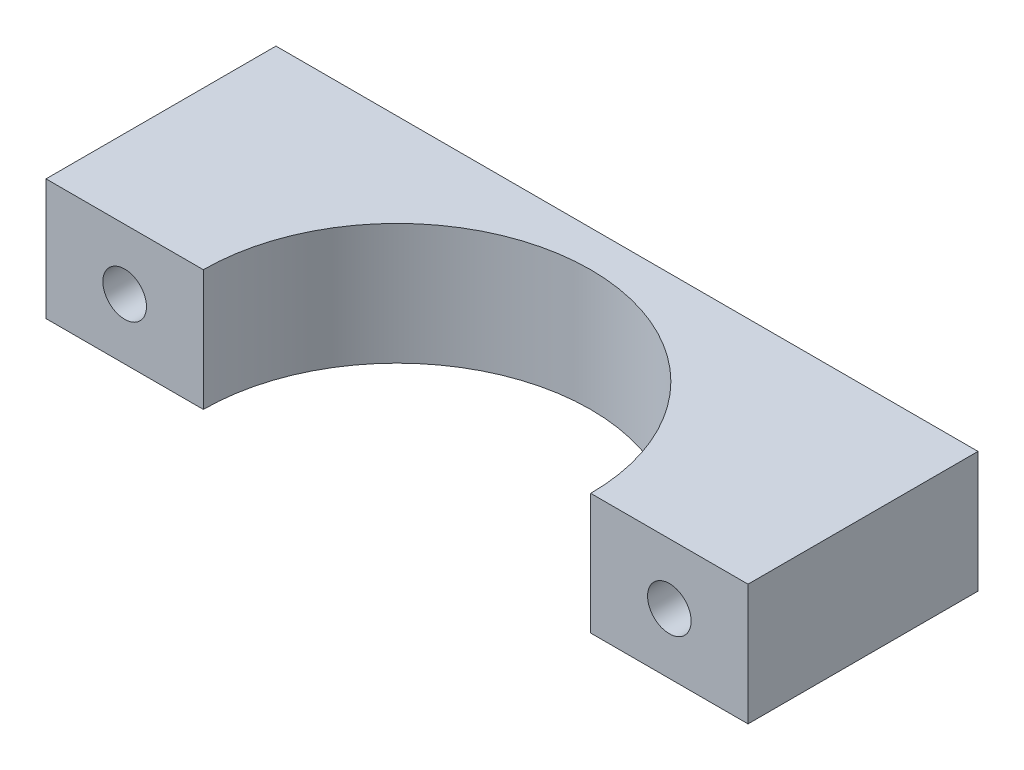
SolidWorks part; units mm, degrees
ref_plane "前视基准面" through (0, 0, 0) normal (0, 0, 1) x (1, 0, 0)
ref_plane "上视基准面" through (0, 0, 0) normal (0, 1, 0) x (1, 0, 0)
ref_plane "右视基准面" through (0, 0, 0) normal (1, 0, 0) x (0, 0, -1)
sketch "草图1" plane through (0, 0, 0) normal (0, 1, 0) x (1, 0, 0)
  line L0 (-29.8076, -12.4255) -> (-3.8076, -12.4255) construction
  line L2 (-69.3343, 8.5745) -> (-11.3343, 8.5745) construction
  line L3 (-69.3343, 8.5745) -> (-69.3343, 4.5745) construction
  line L4 (-69.3343, 4.5745) -> (-11.3343, 4.5745) construction
  line L5 (-11.3343, 8.5745) -> (-11.3343, 4.5745) construction
  line L8 (-69.3343, 6.5745) -> (-56.3343, 6.5745)
  line L10 (-11.3343, 6.5745) -> (-24.3343, 6.5745)
  line L11 (-69.3343, 6.5745) -> (-69.3343, 25.5745)
  line L12 (-69.3343, 25.5745) -> (-11.3343, 25.5745)
  line L13 (-11.3343, 25.5745) -> (-11.3343, 6.5745)
  circle A0 centre (-40.3343, 6.5745) radius 16 construction
  circle A1 centre (-40.3343, 6.5745) radius 19 construction
  arc A3 (-56.3343, 6.5745) -> (-24.3343, 6.5745) centre (-40.3343, 6.5745) cw
  point P9 (-69.3343, 6.5745)
  point P11 (-40.3343, 8.5745)
  dimension "D1" = 4
  dimension "D2" = 29
  dimension "D3" = 19
extrude "凸台-拉伸2" add sketch "草图1" along normal blind 10
sketch "草图8" plane through (0, 0, -6.5745) normal (0, 0, 1) x (1, 0, 0)
  line L0 (-69.3343, 10) -> (-56.3343, 10) construction
  line L1 (-69.3343, 10) -> (-69.3343, 0) construction
  line L2 (-24.3343, 10) -> (-11.3343, 10) construction
  line L3 (-11.3343, 10) -> (-11.3343, 0) construction
  circle A0 centre (-62.8343, 5) radius 1.8
  circle A1 centre (-17.8343, 5) radius 1.8
  point P0 (-62.8343, 10)
  point P1 (-69.3343, 5)
  point P4 (-17.8343, 10)
  point P7 (-11.3343, 5)
  point P10 (-17.8343, 5)
  point P13 (-62.8343, 5)
extrude "切除-拉伸3" cut sketch "草图8" against normal blind 5
sketch "草图9" plane through (0, 0, -25.5745) normal (0, 0, -1) x (-1, 0, 0)
  line L0 (11.3343, 10) -> (11.3343, 0) construction
  line L1 (11.3343, 5) -> (69.3343, 5) construction
  line L2 (69.3343, 10) -> (69.3343, 0) construction
  line L5 (20.7343, 2.1) -> (14.9343, 2.1)
  line L6 (20.7343, 2.1) -> (20.7343, 7.9)
  line L7 (20.7343, 7.9) -> (14.9343, 7.9)
  line L8 (14.9343, 2.1) -> (14.9343, 7.9)
  line L9 (20.7343, 2.1) -> (14.9343, 7.9) construction
  line L10 (20.7343, 7.9) -> (14.9343, 2.1) construction
  line L12 (59.9343, 7.9) -> (65.7343, 7.9)
  line L13 (59.9343, 7.9) -> (59.9343, 2.1)
  line L14 (59.9343, 2.1) -> (65.7343, 2.1)
  line L15 (65.7343, 7.9) -> (65.7343, 2.1)
  line L16 (59.9343, 7.9) -> (65.7343, 2.1) construction
  line L17 (59.9343, 2.1) -> (65.7343, 7.9) construction
  point P0 (11.3343, 5)
  point P7 (62.8343, 5)
  point P9 (17.8343, 5)
  dimension "D1" = 6.5
  dimension "D2" = 5.8
  dimension "D3" = 5.8
  dimension "D4" = 6.5
  dimension "D5" = 5.8
  dimension "D6" = 5.8
extrude "切除-拉伸4" cut sketch "草图9" against normal blind 14
